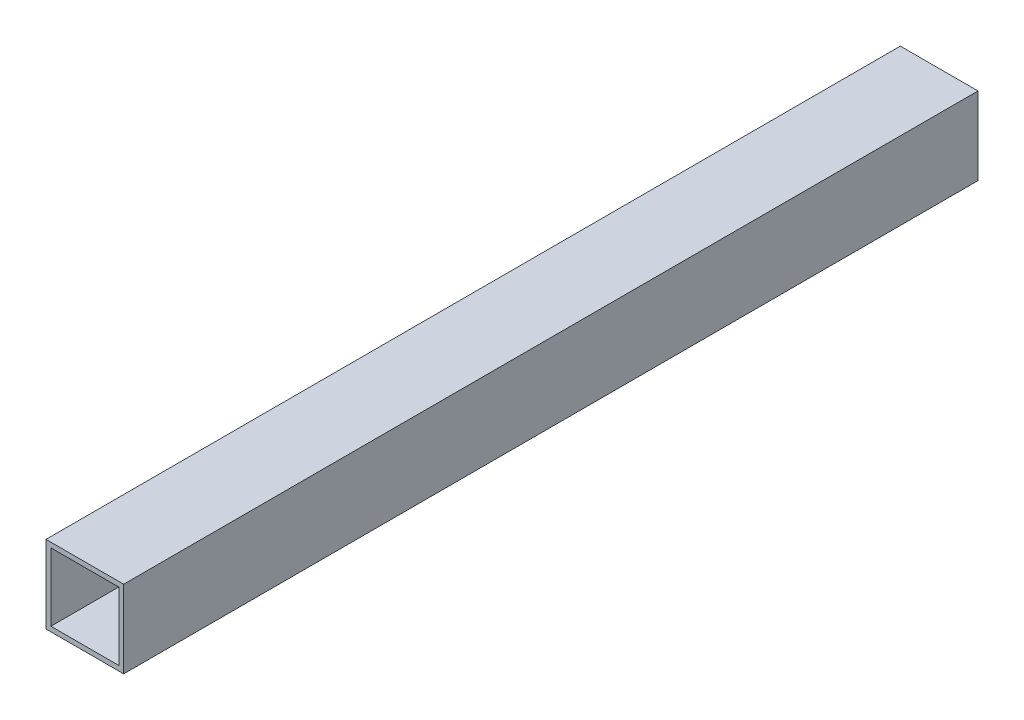
SolidWorks part; units mm, degrees
ref_plane "Front Plane" through (0, 0, 0) normal (0, 0, 1) x (1, 0, 0)
ref_plane "Top Plane" through (0, 0, 0) normal (0, 1, 0) x (1, 0, 0)
ref_plane "Right Plane" through (0, 0, 0) normal (1, 0, 0) x (0, 0, -1)
sketch "Sketch1" plane through (0, 0, 0) normal (0, 0, 1) x (1, 0, 0)
  line L0 (-11.0998, 11.0998) -> (11.0998, 11.0998)
  line L1 (-12.7, -12.7) -> (12.7, -12.7)
  line L2 (-12.7, -12.7) -> (-12.7, 12.7)
  line L3 (-12.7, 12.7) -> (12.7, 12.7)
  line L4 (12.7, -12.7) -> (12.7, 12.7)
  line L5 (-12.7, -12.7) -> (12.7, 12.7) construction
  line L6 (-12.7, 12.7) -> (12.7, -12.7) construction
  line L7 (11.0998, -11.0998) -> (11.0998, 11.0998)
  line L8 (-11.0998, -11.0998) -> (11.0998, -11.0998)
  line L9 (-11.0998, -11.0998) -> (-11.0998, 11.0998)
  point P0 (0, 0)
  dimension "D1" = 25.4
  dimension "D2" = 1.6002
extrude "Boss-Extrude1" add sketch "Sketch1" along normal blind 279.4 contours L9 L8 L7 L0 | L2 L1 L4 L3
equation "\"Length\"= 11"
equation "\"D1@Boss-Extrude1\"=\"Length\""
